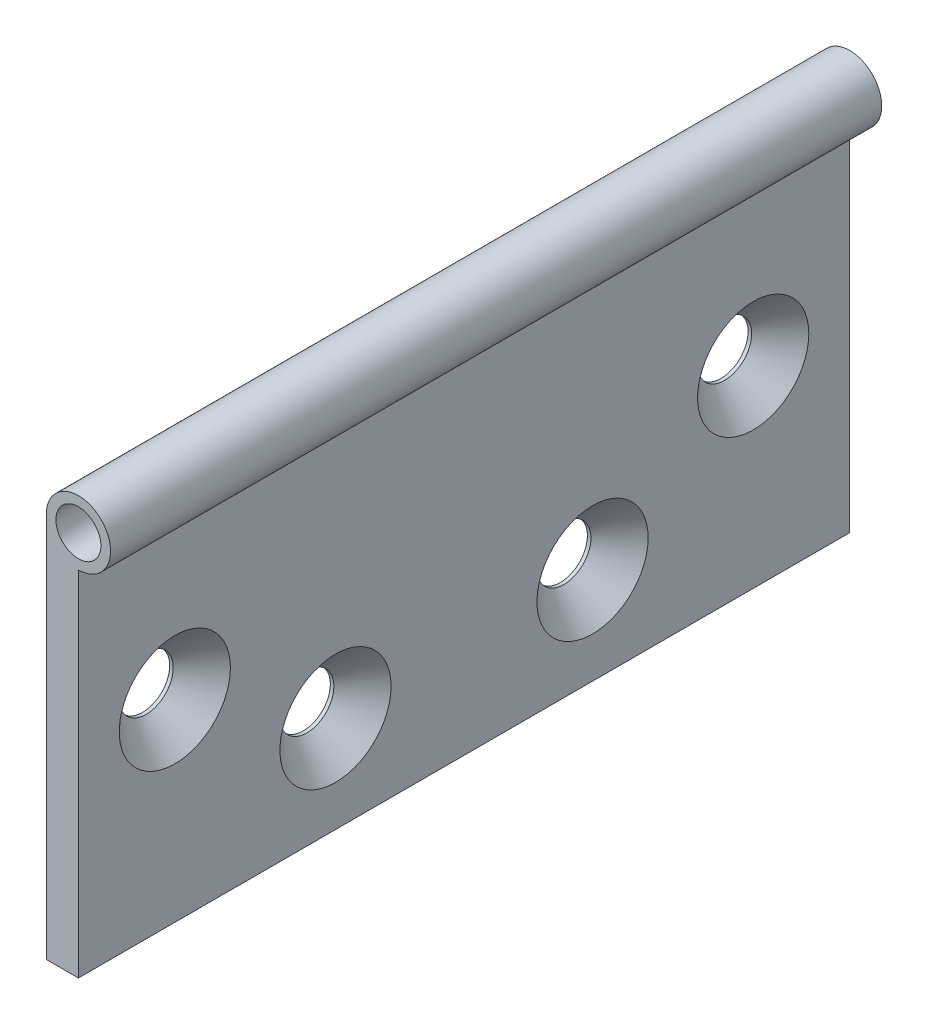
SolidWorks part; units mm, degrees
ref_plane "Front Plane" through (0, 0, 0) normal (0, 0, 1) x (1, 0, 0)
ref_plane "Top Plane" through (0, 0, 0) normal (0, 1, 0) x (1, 0, 0)
ref_plane "Right Plane" through (0, 0, 0) normal (1, 0, 0) x (0, 0, -1)
sketch "Sketch2" plane through (0, 0, 0) normal (0, 0, 1) x (1, 0, 0)
  line L0 (0, 0) -> (0, 60)
  dimension "D1" = 60
extrude "Extrude-Thin1" add sketch "Sketch2" along normal mid plane 120 thin
sketch "Sketch3" plane through (0, 0, 60) normal (0, 0, 1) x (1, 0, 0)
  circle A0 centre (5, 60) radius 5
sweep "Sweep1" add profiles "Sketch3" path edge at (5, 60, 0)
sketch "Sketch4" plane through (0, 0, 60) normal (0, 0, 1) x (1, 0, 0)
  circle A0 centre (5, 60) radius 3.5
  dimension "D1" = 7
extrude "Cut-Extrude1" cut sketch "Sketch4" against normal through all
hole_wizard "CSK for M8 Flat Head Machine Screw1" positions "Sketch5" profile "Sketch6" countersink size "M8" standard "ANSI Metric" end condition through all
sketch "Sketch5" plane through (5, 0, 0) normal (1, 0, 0) x (0, 0, -1)
  line L0 (-60, 0) -> (-60, 55) construction
  line L1 (-60, 0) -> (60, 0) construction
  point P0 (-20, 15)
  point P2 (-45, 30)
  dimension "D1" = 15
  dimension "D2" = 40
  dimension "D3" = 15
  dimension "D4" = 30
sketch "Sketch6" plane through (5, 15, 20) normal (0, 1, 0) x (0, 0, -1)
  line L0 (0, 0) -> (0, 5)
  line L1 (0, 5) -> (4.2, 5)
  line L2 (4.2, 5) -> (4.2, 4.45)
  line L3 (4.2, 4.45) -> (8.65, 0)
  line L5 (8.65, 0) -> (0, 0)
  line L6 (-4.2, 4.45) -> (-8.65, 0) construction
  line L11 (0, -6.35) -> (0, 107.95) construction
  dimension "Thru Hole Dia." = 8.4
  dimension "Thru Hole Depth" = 5
  dimension "Near C'Sink Dia." = 17.3
  dimension "Near C'Sink Angle" = 90
mirror "Mirror1" about plane through (0, 0, 0) normal (0, 0, 1) of "CSK for M8 Flat Head Machine Screw1"
sketch "layoutcuts" plane through (5, 0, 0) normal (1, 0, 0) x (0, 0, -1)
  line L1 (60, 55) -> (60, 65) construction
  line L2 (-60, 54) -> (60, 54)
  line L3 (-60, 54) -> (60, 54)
  line L4 (-60, 65) -> (-60, 55) construction
  line L5 (60, 54) -> (60, 65)
  line L6 (-60, 65) -> (-60, 54)
  line L7 (-60, 65) -> (60, 65)
  line L8 (-36, 54) -> (-36, 65)
  line L9 (-12, 54) -> (-12, 65)
  dimension "D2" = 24
  dimension "D3" = 24
  dimension "D1" = 1
sketch "Sketch8" plane through (5, 0, 0) normal (1, 0, 0) x (0, 0, -1)
  line L0 (-60, 54) -> (60, 54) construction
  line L1 (60, 54) -> (60, 65) construction
  line L2 (-60, 65) -> (60, 65) construction
  line L3 (-60, 65) -> (-60, 54) construction
  line L4 (60, 55) -> (-60, 55)
  line L5 (-60, 55) -> (-60, 0)
  line L6 (-60, 0) -> (60, 0)
  line L7 (60, 0) -> (60, 55)
  line L8 (60, 55) -> (-60, 55)
  line L9 (-60, 55) -> (-60, 0)
  line L10 (-60, 0) -> (60, 0)
  line L11 (60, 0) -> (60, 55)
  line L12 (-60, 54) -> (60, 54)
  line L13 (60, 54) -> (60, 65)
  line L14 (-60, 65) -> (60, 65)
  line L15 (-60, 65) -> (-60, 54)
  line L18 (-37, 54) -> (-37, 65)
  line L19 (-37, 54) -> (-37, 65)
  line L21 (-13, 54) -> (-13, 65)
  line L22 (-13, 54) -> (-13, 65)
  dimension "D1" = 0
  dimension "D2" = 1
  dimension "D3" = 1
equation "\"D4@Sketch5\" = \"D1@Sketch2\" / 2"
equation "\"D2@Sketch5\"= \"D1@Extrude-Thin1\" / 3"
equation "\"D2@layoutcuts\"= \"D1@Extrude-Thin1\" / 5"
equation "\"D3@layoutcuts\"= \"D1@Extrude-Thin1\" / 5"
